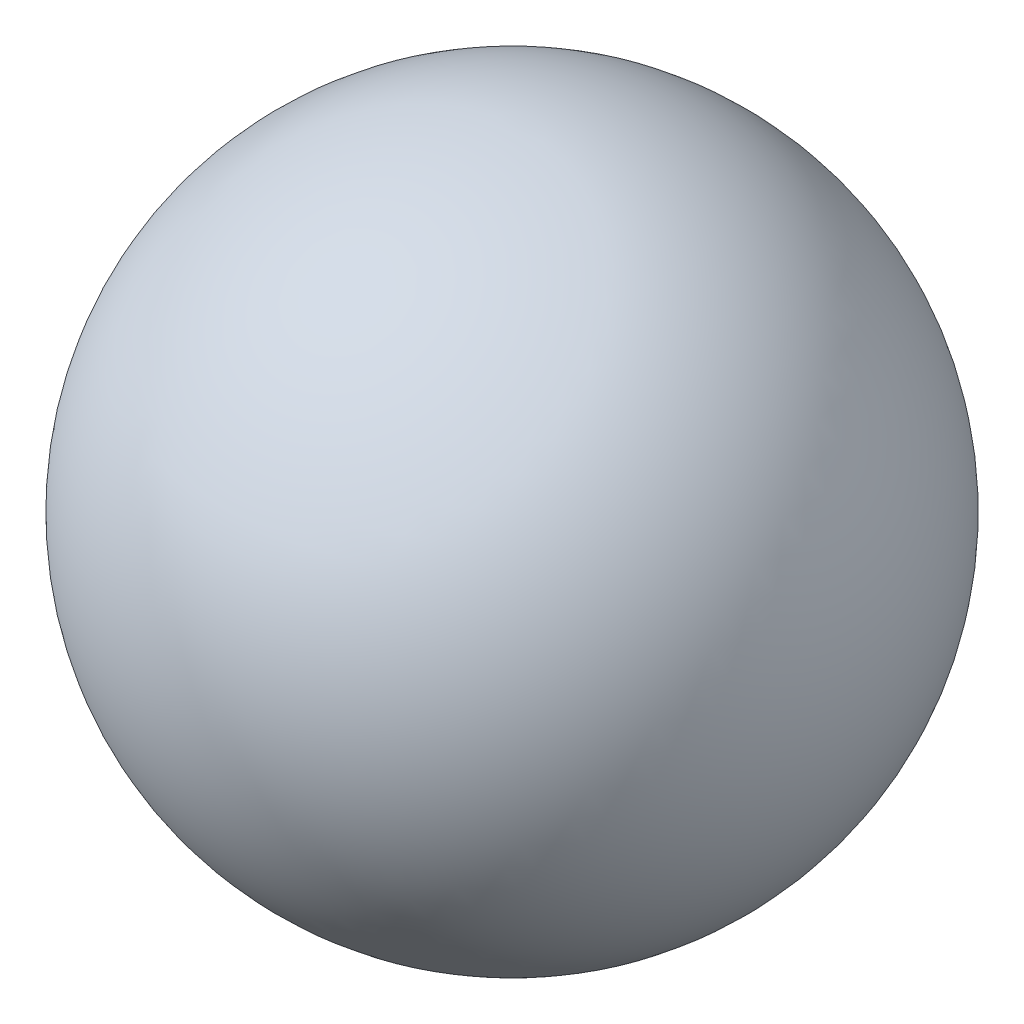
SolidWorks part; units mm, degrees
ref_plane "Front Plane" through (0, 0, 0) normal (0, 0, 1) x (1, 0, 0)
ref_plane "Top Plane" through (0, 0, 0) normal (0, 1, 0) x (1, 0, 0)
ref_plane "Right Plane" through (0, 0, 0) normal (1, 0, 0) x (0, 0, -1)
sketch "Sketch1" plane through (0, 0, 0) normal (0, 0, 1) x (1, 0, 0)
  line L0 (0, 21) -> (0, -21)
  arc A0 (0, -21) -> (0, 21) centre (0, 0) ccw
  dimension "D1" = 42
revolve "Revolve1" add sketch "Sketch1" angle 360 about L0
